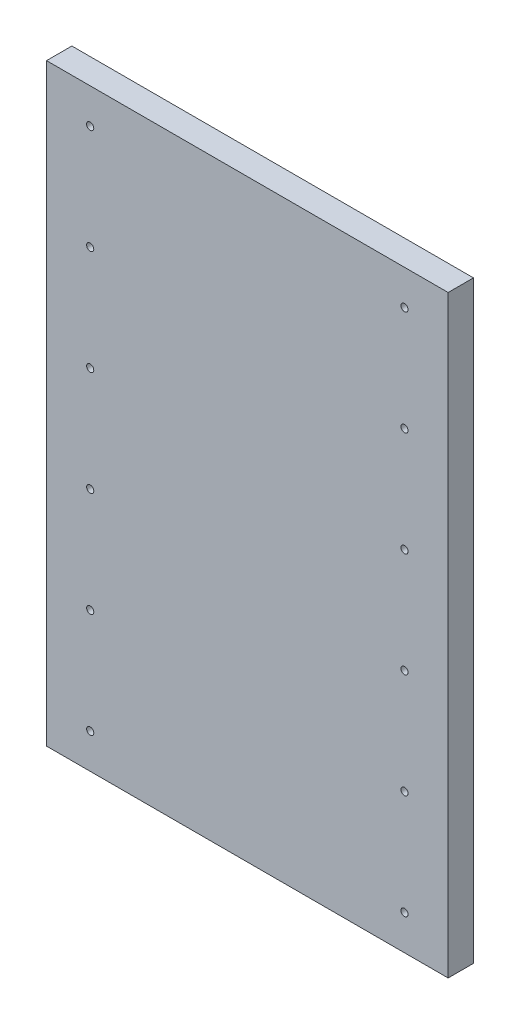
SolidWorks part; units mm, degrees
ref_plane "Plan de face" through (0, 0, 0) normal (0, 0, 1) x (1, 0, 0)
ref_plane "Plan de dessus" through (0, 0, 0) normal (0, 1, 0) x (1, 0, 0)
ref_plane "Plan de droite" through (0, 0, 0) normal (1, 0, 0) x (0, 0, -1)
sketch "Esquisse1" plane through (0, 0, 0) normal (0, 0, 1) x (1, 0, 0)
  line L1 (0, 0) -> (230, 0)
  line L2 (0, 0) -> (0, 340)
  line L3 (0, 340) -> (230, 340)
  line L4 (230, 0) -> (230, 340)
  dimension "D1" = 230
  dimension "D2" = 340
extrude "Boss.-Extru.1" add sketch "Esquisse1" along normal blind 14.5
sketch "Esquisse2" plane through (0, 0, 14.5) normal (0, 0, 1) x (1, 0, 0)
  line L0 (115, 0) -> (115, 340) construction
  line L1 (0, 0) -> (230, 0) construction
  line L2 (230, 340) -> (0, 340) construction
  line L3 (25, 0) -> (25, 340) construction
  line L4 (205, 0) -> (205, 340) construction
  circle A0 centre (25, 20) radius 2.05
  circle A1 centre (25, 80) radius 2.05
  circle A2 centre (25, 140) radius 2.05
  circle A3 centre (25, 200) radius 2.05
  circle A4 centre (25, 260) radius 2.05
  circle A5 centre (25, 320) radius 2.05
  circle A6 centre (205, 320) radius 2.05
  circle A7 centre (205, 260) radius 2.05
  circle A8 centre (205, 200) radius 2.05
  circle A9 centre (205, 140) radius 2.05
  circle A10 centre (205, 80) radius 2.05
  circle A11 centre (205, 20) radius 2.05
  point P10 (20, 92.5518)
  dimension "D1" = 4.1
  dimension "D4" = 20
  dimension "D5" = 60
  dimension "D3" = 90
  dimension "D2" = 6
extrude "Enlèv. mat.-Extru.1" cut sketch "Esquisse2" against normal through all both and the other way through all
